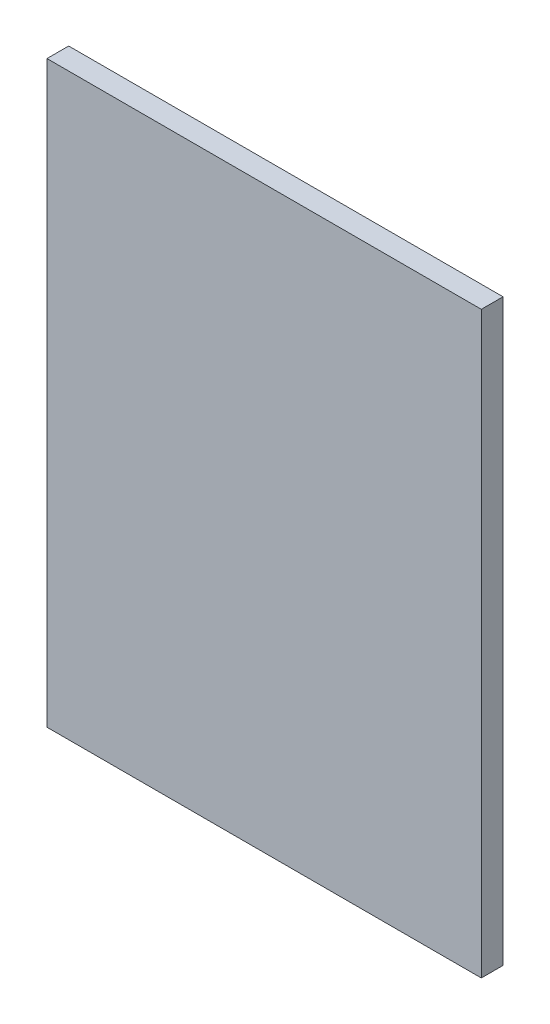
SolidWorks part; units mm, degrees
material "Glass"
ref_plane "Front Plane" through (0, 0, 0) normal (0, 0, 1) x (1, 0, 0)
ref_plane "Top Plane" through (0, 0, 0) normal (0, 1, 0) x (1, 0, 0)
ref_plane "Right Plane" through (0, 0, 0) normal (1, 0, 0) x (0, 0, -1)
sketch "Sketch1" plane through (0, 0, 0) normal (0, 0, 1) x (1, 0, 0)
  line L1 (0, 0) -> (60, 0)
  line L2 (0, 0) -> (0, -80)
  line L3 (0, -80) -> (60, -80)
  line L4 (60, 0) -> (60, -80)
  dimension "D1" = 60
  dimension "D2" = 80
extrude "Boss-Extrude1" add sketch "Sketch1" along normal blind 3
